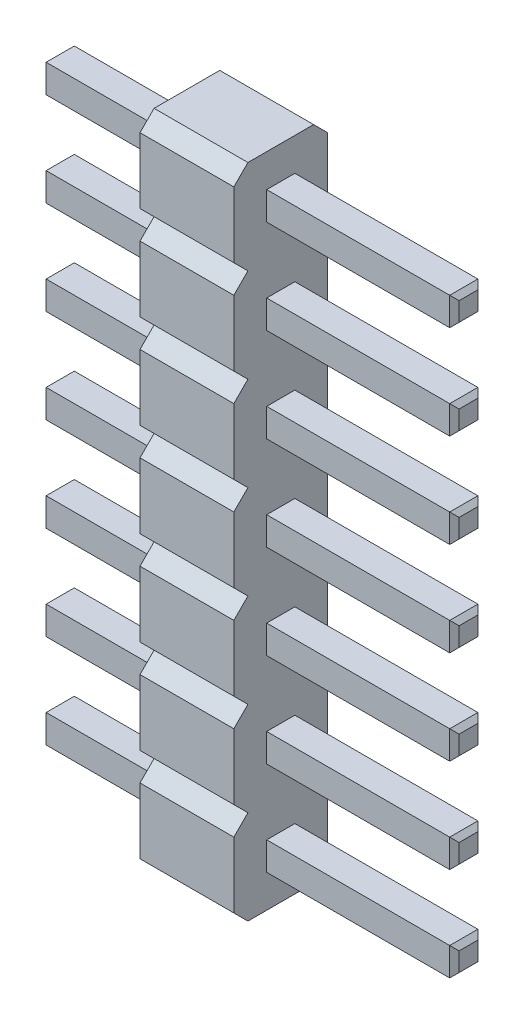
SolidWorks part; units mm, degrees
ref_plane "Front Plane" through (0, 0, 0) normal (0, 0, 1) x (1, 0, 0)
ref_plane "Top Plane" through (0, 0, 0) normal (0, 1, 0) x (1, 0, 0)
ref_plane "Right Plane" through (0, 0, 0) normal (1, 0, 0) x (0, 0, -1)
sketch "Sketch1" plane through (0, 0, 0) normal (1, 0, 0) x (0, 0, -1)
  line L0 (0, 0) -> (-1, 0) construction
  line L5 (-1, 0) -> (-1, 1) construction
  line L6 (-1.7, 1) -> (-0.3, 1)
  line L7 (-0.3, 1) -> (0, 0.7)
  line L8 (0, 0.7) -> (0, -0.7)
  line L9 (-2, 0.7) -> (-2, -0.7)
  line L10 (-1.7, 1) -> (-2, 0.7)
  line L11 (-0.3, -1) -> (0, -0.7)
  line L12 (-1.7, -1) -> (-0.3, -1)
  line L13 (-1.7, -1) -> (-2, -0.7)
  point P13 (-2, 0)
  dimension "D1" = 1
  dimension "D2" = 45
  dimension "D3" = 0.3
extrude "Plastic" add sketch "Sketch1" along normal blind 2
sketch "Sketch2" plane through (0, 0, 0) normal (0, 1, 0) x (1, 0, 0)
  line L0 (-2.8, -0.7) -> (-2.8, -1.3)
  line L1 (-2.8, -1) -> (6, -1) construction
  line L2 (0, -1.7) -> (0, -0.3) construction
  line L4 (-2.8, -1.3) -> (6, -1.3)
  line L6 (-2.8, -0.7) -> (6, -0.7)
  line L8 (6, -1.3) -> (6, -0.7)
  line L9 (2, -0.3) -> (2, -1.7) construction
  line L11 (-3.4, 3.63) -> (-3.4, -0.4) construction
  line L12 (-3.7, 3.63) -> (-3.7, -0.4) construction
  line L13 (-3.1, 3.63) -> (-3.1, -0.4) construction
  arc A3 (-3.7, -0.4) -> (-2.8, -1.3) centre (-2.8, -0.4) ccw construction
  arc A4 (-3.4, -0.4) -> (-2.8, -1) centre (-2.8, -0.4) ccw construction
  arc A5 (-3.1, -0.4) -> (-2.8, -0.7) centre (-2.8, -0.4) ccw construction
  point P5 (0, -1)
  dimension "D1" = 4
  dimension "D4" = 2.8
  dimension "D2" = 0.3
  dimension "D3" = 0.3
extrude "Contact" add sketch "Sketch2" along normal mid plane 0.6
chamfer "Chamfer1" distance 0.1 angle 45 8 edges at (6, 0.3, 1) (6, 0, 1.3) (6, -0.3, 1) (6, 0, 0.7) (-2.8, -0.3, 1) (-2.8, 0, 0.7) (-2.8, 0.3, 1) (-2.8, 0, 1.3)
pattern_linear "LPattern1" count 7 spacing 2 along (0, 1, 0) of "Plastic", "Contact", "Chamfer1"
